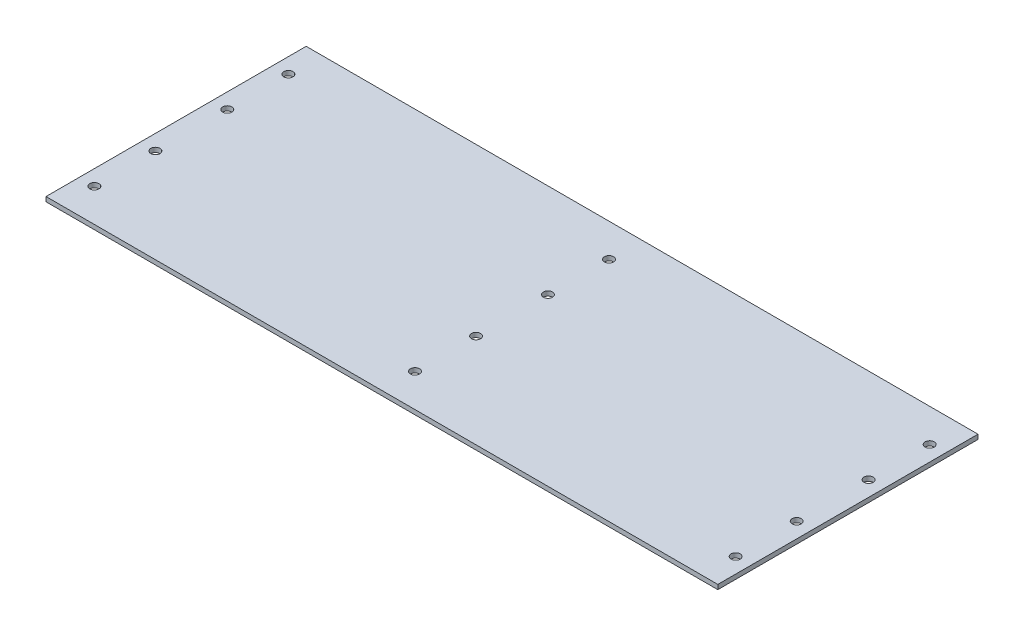
SolidWorks part; units mm, degrees
ref_plane "前视基准面" through (0, 0, 0) normal (0, 0, 1) x (1, 0, 0)
ref_plane "上视基准面" through (0, 0, 0) normal (0, 1, 0) x (1, 0, 0)
ref_plane "右视基准面" through (0, 0, 0) normal (1, 0, 0) x (0, 0, -1)
sketch "草图1" plane through (0, 0, 0) normal (0, 1, 0) x (1, 0, 0)
  line L1 (-65.705, 44.3173) -> (154.295, 44.3173)
  line L2 (-65.705, 44.3173) -> (-65.705, -40.8827)
  line L3 (-65.705, -40.8827) -> (154.295, -40.8827)
  line L4 (154.295, 44.3173) -> (154.295, -40.8827)
  dimension "D1" = 85.2
  dimension "D2" = 220
extrude "凸台-拉伸1" add sketch "草图1" along normal blind 1.5
sketch "草图2" plane through (0, 1.5, 0) normal (0, 1, 0) x (1, 0, 0)
  line L0 (-65.705, -40.8827) -> (154.295, -40.8827) construction
  line L1 (154.295, -40.8827) -> (154.295, 44.3173) construction
  line L2 (-65.705, 1.7173) -> (154.295, 1.7173)
  line L3 (-65.705, 44.3173) -> (-65.705, -40.8827) construction
  circle A0 centre (149.295, -30.0527) radius 1.5
  circle A1 centre (44.295, -30.0527) radius 1.5
  circle A2 centre (-60.705, -30.0527) radius 1.5
  circle A3 centre (44.295, -10.0527) radius 1.5
  circle A4 centre (-60.705, -10.0527) radius 1.5
  circle A5 centre (149.295, -10.0527) radius 1.5
  circle A6 centre (149.295, 13.4873) radius 1.5
  circle A7 centre (-60.705, 13.4873) radius 1.5
  circle A8 centre (44.295, 13.4873) radius 1.5
  circle A9 centre (-60.705, 33.4873) radius 1.5
  circle A10 centre (44.295, 33.4873) radius 1.5
  circle A11 centre (149.295, 33.4873) radius 1.5
  dimension "D2" = 5
  dimension "D3" = 3
  dimension "D1" = 10.83
  dimension "D4" = 3
  dimension "D5" = 2
extrude "切除-拉伸1" cut sketch "草图2" against normal blind 10 contours A0 | A5 | A3 | A1 | A8 | A10 | A6 | A11 | A9 | A7 | A4 | A2
